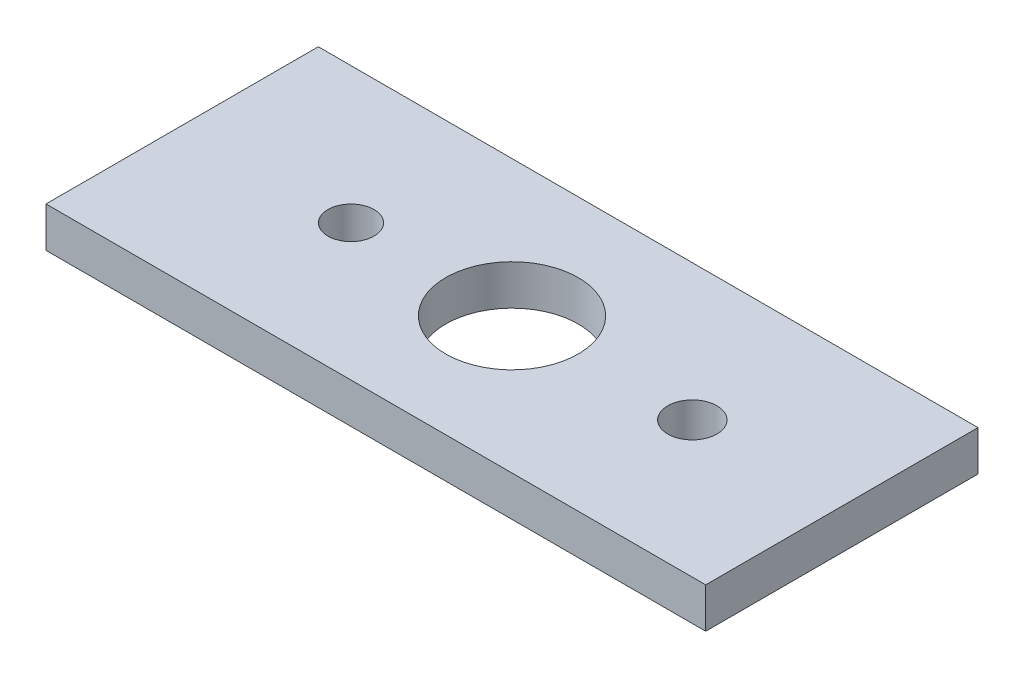
SolidWorks part; units mm, degrees
ref_plane "Front Plane" through (0, 0, 0) normal (0, 0, 1) x (1, 0, 0)
ref_plane "Top Plane" through (0, 0, 0) normal (0, 1, 0) x (1, 0, 0)
ref_plane "Right Plane" through (0, 0, 0) normal (1, 0, 0) x (0, 0, -1)
sketch "Sketch1" plane through (0, 0, 0) normal (0, 1, 0) x (1, 0, 0)
  line L1 (82.0281, -33.859) -> (-82.0281, -33.859)
  line L2 (82.0281, -33.859) -> (82.0281, 33.859)
  line L3 (82.0281, 33.859) -> (-82.0281, 33.859)
  line L4 (-82.0281, -33.859) -> (-82.0281, 33.859)
  line L5 (82.0281, -33.859) -> (-82.0281, 33.859) construction
  line L6 (82.0281, 33.859) -> (-82.0281, -33.859) construction
  point P0 (0, 0)
extrude "Boss-Extrude1" add sketch "Sketch1" along normal blind 10
sketch "Sketch2" plane through (0, 10, 0) normal (0, 1, 0) x (1, 0, 0)
  circle A0 centre (-40.0431, 0) radius 5.7334
extrude "Cut-Extrude1" cut sketch "Sketch2" against normal blind 10
sketch "Sketch4" plane through (0, 10, 0) normal (0, 1, 0) x (1, 0, 0)
  line L0 (-5.5, 0) -> (5.5, 0) construction
  circle A0 centre (44.8483, 0) radius 6.1066
extrude "Cut-Extrude2" cut sketch "Sketch4" against normal blind 10
sketch "Sketch6" plane through (0, 10, 0) normal (0, 1, 0) x (1, 0, 0)
  circle A0 centre (0, 0) radius 16.4723
extrude "Cut-Extrude3" cut sketch "Sketch6" against normal blind 10
